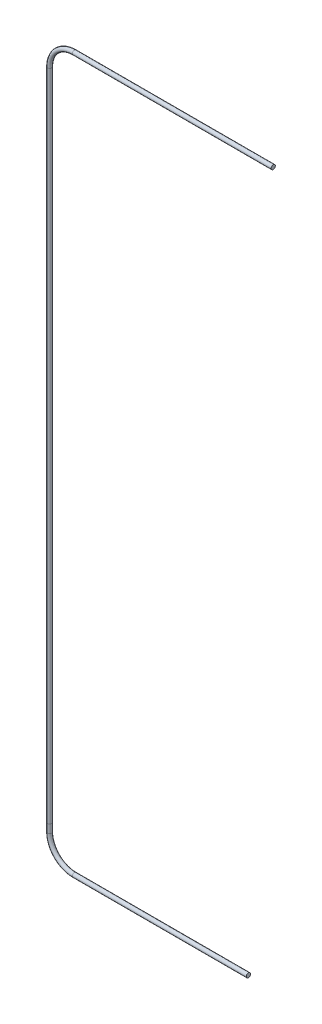
SolidWorks part; units mm, degrees
ref_plane "Front Plane" through (0, 0, 0) normal (0, 0, 1) x (1, 0, 0)
ref_plane "Top Plane" through (0, 0, 0) normal (0, 1, 0) x (1, 0, 0)
ref_plane "Right Plane" through (0, 0, 0) normal (1, 0, 0) x (0, 0, -1)
sketch "Sketch1" plane through (0, 0, 0) normal (0, 0, 1) x (1, 0, 0)
  line L0 (0, 0) -> (0, 1975)
  line L1 (75, 2050) -> (675, 2050)
  line L2 (0, 0) -> (0, -25)
  line L3 (75, -100) -> (600, -100)
  arc A0 (75, -100) -> (0, -25) centre (75, -25) cw
  arc A1 (75, 2050) -> (0, 1975) centre (75, 1975) ccw
  point P7 (0, -100)
  dimension "D3" = 75
  dimension "D4" = 75
  dimension "D1" = 100
  dimension "D2" = 600
  dimension "D5" = 600
  dimension "D6" = 2050
sweep "Sweep1" add path "Sketch1" circular profile diameter 12.7 parameters "D3"=12.7
